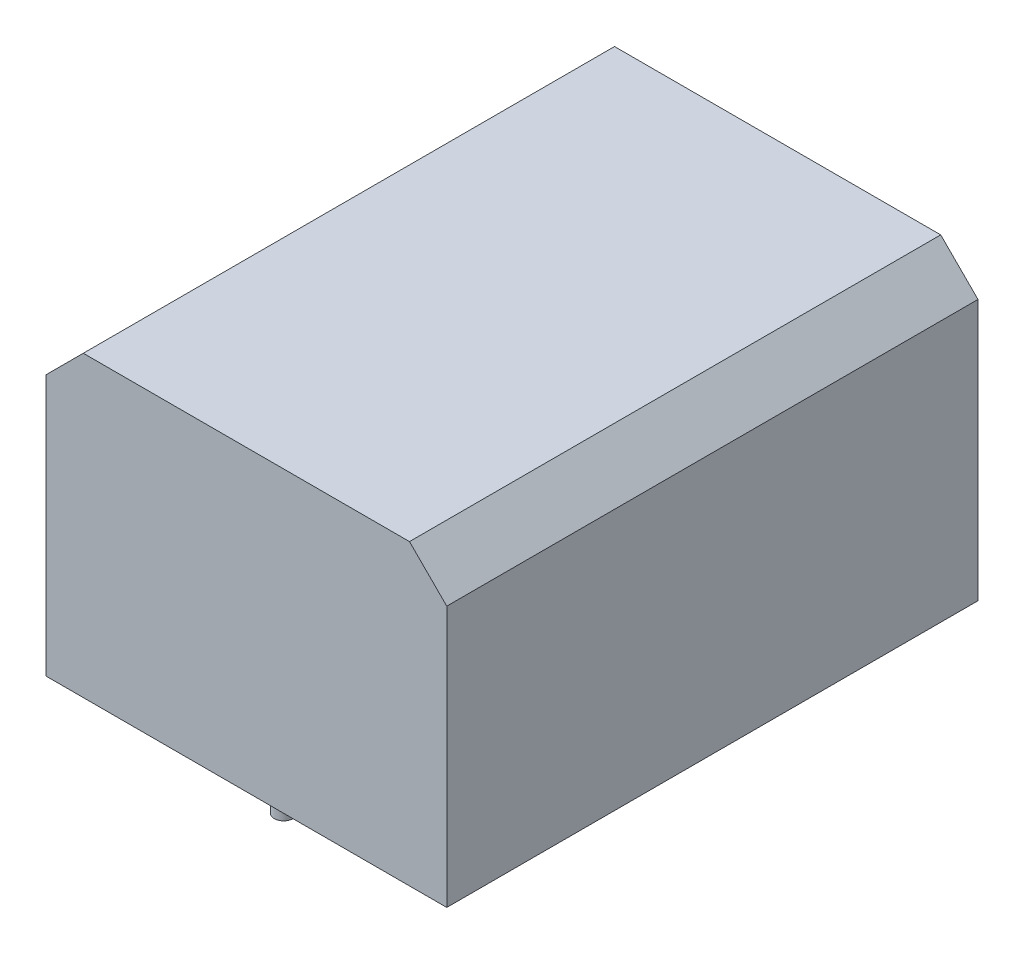
SolidWorks part; units mm, degrees
ref_plane "Спереди" through (0, 0, 0) normal (0, 0, 1) x (1, 0, 0)
ref_plane "Сверху" through (0, 0, 0) normal (0, 1, 0) x (1, 0, 0)
ref_plane "Справа" through (0, 0, 0) normal (1, 0, 0) x (0, 0, -1)
sketch "Эскиз1" plane through (0, 0, 0) normal (0, 0, 1) x (1, 0, 0)
  line L0 (-10.75, 0) -> (10.75, 0)
  line L1 (10.75, 0) -> (10.75, 14)
  line L2 (10.75, 14) -> (8.75, 16)
  line L3 (8.75, 16) -> (-8.75, 16)
  line L4 (-8.75, 16) -> (-10.75, 14)
  line L5 (-10.75, 14) -> (-10.75, 0)
  dimension "D1" = 16
  dimension "D2" = 14
  dimension "D3" = 14
  dimension "D4" = 2
  dimension "D5" = 2
  dimension "D6" = 21.5
  dimension "D7" = 10.75
extrude "Бобышка-Вытянуть2" add sketch "Эскиз1" along normal mid plane 28.5
sketch "Эскиз2" plane through (0, 0, 0) normal (0, -1, 0) x (1, 0, 0)
  circle A0 centre (0, 12.25) radius 0.5
  circle A1 centre (0, -12.25) radius 0.5
  dimension "D1" = 1
  dimension "D2" = 1
  dimension "D3" = 24.5
  dimension "D4" = 12.25
extrude "Бобышка-Вытянуть3" add sketch "Эскиз2" along normal blind 2
equation "\"H\" = 16"
equation "\"D1@Эскиз1\"= \"H\""
equation "\"B\"= \"H\" - 2"
equation "\"D2@Эскиз1\"=\"B\""
equation "\"D3@Эскиз1\"=\"B\""
equation "\"W\" = 21.5"
equation "\"D6@Эскиз1\"=\"W\""
equation "\"W_2\" = \"W\" / 2"
equation "\"D7@Эскиз1\"=\"W_2\""
equation "\"L\" = 28.5"
equation "\"D1@Бобышка-Вытянуть2\"=\"L\""
equation "\"Fd\"= 1"
equation "\"D1@Эскиз2\"=\"Fd\""
equation "\"D2@Эскиз2\"=\"Fd\""
equation "\"P\" = 24.5"
equation "\"D3@Эскиз2\"=\"P\""
equation "\"P_2\"= \"P\" / 2"
equation "\"D4@Эскиз2\"=\"P_2\""
